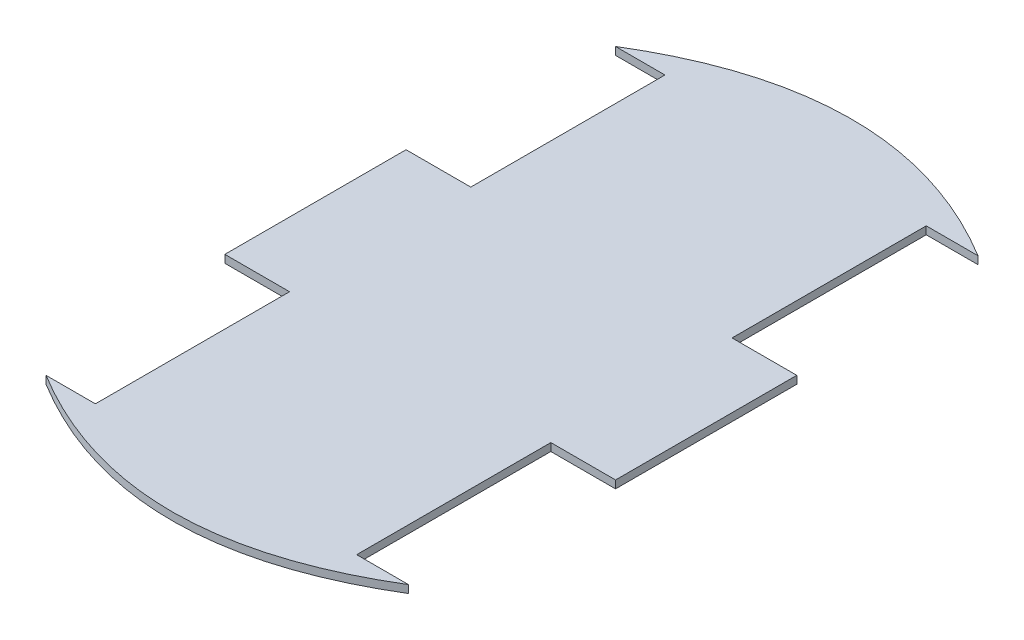
SolidWorks part; units mm, degrees
ref_plane "前视基准面" through (0, 0, 0) normal (0, 0, 1) x (1, 0, 0)
ref_plane "上视基准面" through (0, 0, 0) normal (0, 1, 0) x (1, 0, 0)
ref_plane "右视基准面" through (0, 0, 0) normal (1, 0, 0) x (0, 0, -1)
other "Configuration Table"
sketch "草图1" plane through (0, 0, 0) normal (0, 1, 0) x (1, 0, 0)
  line L4 (-49.9877, 0) -> (-49.9877, 75)
  line L5 (50.9359, 0) -> (50.9359, 75)
  line L6 (-49.9877, 75) -> (-69.0641, 75)
  line L7 (50.9359, 75) -> (70.9359, 75)
  line L8 (50.9359, 0) -> (75.9359, 0)
  line L9 (-49.9877, 0) -> (-74.9877, 0)
  line L10 (-74.9877, 0) -> (-74.9877, -70)
  line L11 (75.9359, 0) -> (75.9359, -70)
  line L13 (50.9359, -70) -> (75.9359, -70)
  line L14 (-49.9877, -70) -> (-74.9877, -70)
  line L16 (-49.9877, -70) -> (-49.9877, -145)
  line L17 (50.9359, -70) -> (50.9359, -145)
  line L18 (50.9359, -145) -> (70.9359, -145)
  line L19 (-49.9877, -145) -> (-69.0641, -145)
  spline S0 degree 2 poles (-69.0641, 75) (0.7774, 117.5828) (70.9359, 75) knots 0 0 0 1 1 1
  spline S1 degree 2 poles (-69.0641, -145) (0.7774, -187.5828) (70.9359, -145) knots 0 0 0 1 1 1
extrude "凸台-拉伸1" add sketch "草图1" along normal blind 3
